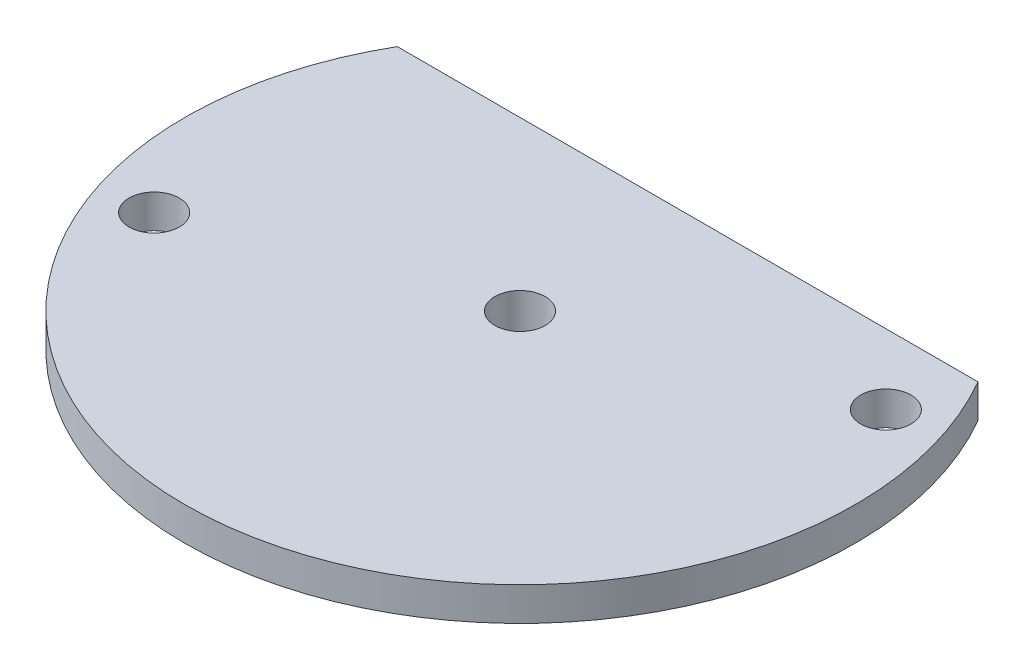
SolidWorks part; units mm, degrees
ref_plane "Alzado" through (0, 0, 0) normal (0, 0, 1) x (1, 0, 0)
ref_plane "Planta" through (0, 0, 0) normal (0, 1, 0) x (1, 0, 0)
ref_plane "Vista lateral" through (0, 0, 0) normal (1, 0, 0) x (0, 0, -1)
sketch "Croquis1" plane through (0, 0, 0) normal (0, 1, 0) x (1, 0, 0)
  line L0 (-17.3205, 10) -> (17.3205, 10)
  line L1 (0, 0) -> (-18.7939, -6.8404) construction
  line L2 (0, 0) -> (18.7939, 6.8404) construction
  line L3 (0, 0) -> (20, 0) construction
  arc A0 (-17.3205, 10) -> (17.3205, 10) centre (0, 0) ccw
  arc A1 (17.3205, 10) -> (-17.3205, 10) centre (0, 0) ccw construction
  circle A2 centre (-16, -5.8235) radius 1.5
  circle A3 centre (16, 5.8235) radius 1.5
  dimension "D2" = 40
  dimension "D4" = 3
  dimension "D5" = 3
  dimension "D1" = 10
  dimension "D3" = 20
  dimension "D6" = 16
  dimension "D7" = 32
extrude "Saliente-Extruir1" add sketch "Croquis1" along normal blind 2
sketch "Croquis2" plane through (0, 0, 0) normal (0, 1, 0) x (1, 0, 0)
  circle A0 centre (0, 0) radius 3
  circle A1 centre (0, 0) radius 1.5
  point P5 (-0.271, 0)
  dimension "D1" = 3
  dimension "D2" = 6
extrude "Saliente-Extruir3" add sketch "Croquis2" against normal blind 6
sketch "Croquis4" plane through (0, 0, 0) normal (0, -1, 0) x (1, 0, 0)
  circle A1 centre (0, 0) radius 1.5
  circle A2 centre (0, 0) radius 1.5
  dimension "D1" = 0
extrude "Cortar-Extruir2" cut sketch "Croquis4" against normal blind 6
